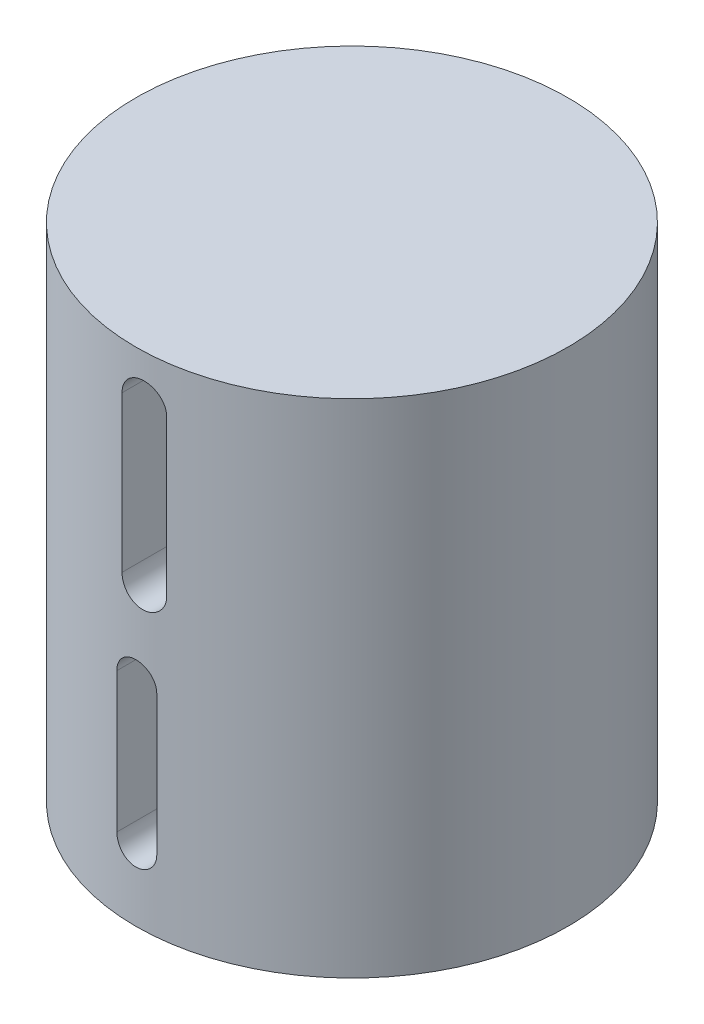
SolidWorks part; units mm, degrees
ref_plane "前视基准面" through (0, 0, 0) normal (0, 0, 1) x (1, 0, 0)
ref_plane "上视基准面" through (0, 0, 0) normal (0, 1, 0) x (1, 0, 0)
ref_plane "右视基准面" through (0, 0, 0) normal (1, 0, 0) x (0, 0, -1)
sketch "草图1" plane through (0, 0, 0) normal (0, 1, 0) x (1, 0, 0)
  circle A0 centre (0, 0) radius 27.9917
ref_plane "基准面1" through (0, 10, 0) normal (0, 1, 0) x (1, 0, 0)
sketch "草图3" plane through (0, 10, 0) normal (0, 1, 0) x (1, 0, 0)
  circle A0 centre (0, 0) radius 27.9917 construction
  circle A1 centre (0, 0) radius 27.9917
extrude "凸台-拉伸1" add sketch "草图3" along normal blind 65
ref_plane "基准面2" through (0, 0, 27.9917) normal (0, 0, 1) x (1, 0, 0)
sketch "草图4" plane through (0, 0, 27.9917) normal (0, 0, 1) x (1, 0, 0)
  line L0 (0.9428, 68.919) -> (0.9428, 48.769) construction
  line L1 (3.7444, 68.919) -> (3.7444, 48.769)
  line L2 (-1.8588, 68.919) -> (-1.8588, 48.769)
  arc A0 (3.7444, 68.919) -> (-1.8588, 68.919) centre (0.9428, 68.919) ccw
  arc A1 (-1.8588, 48.769) -> (3.7444, 48.769) centre (0.9428, 48.769) ccw
  point P2 (0.9428, 58.844)
extrude "切除-拉伸1" cut sketch "草图4" against normal blind 27 contours L2 A1 L1 A0
sketch "草图6" plane through (0, 0, 0) normal (0, 0, 1) x (1, 0, 0)
  line L0 (0, 37.3471) -> (0, 19.2444) construction
  line L1 (2.5861, 37.3471) -> (2.5861, 19.2444)
  line L2 (-2.5861, 37.3471) -> (-2.5861, 19.2444)
  arc A0 (2.5861, 37.3471) -> (-2.5861, 37.3471) centre (0, 37.3471) ccw
  arc A1 (-2.5861, 19.2444) -> (2.5861, 19.2444) centre (0, 19.2444) ccw
  point P3 (0, 28.2957)
extrude "切除-拉伸3" cut sketch "草图6" along normal blind 50
